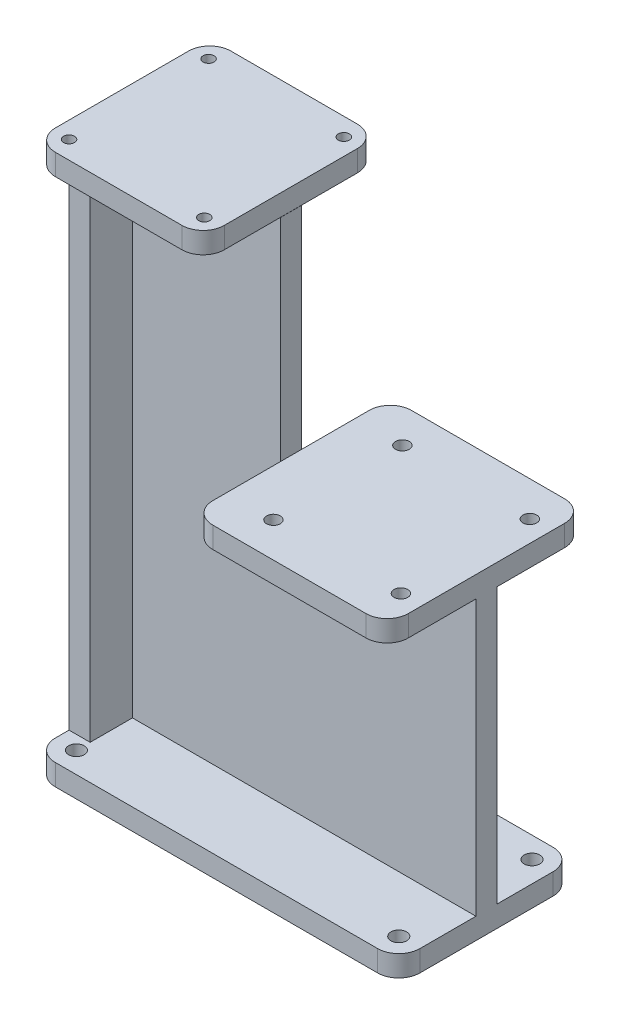
SolidWorks part; units mm, degrees
ref_plane "Front Plane" through (0, 0, 0) normal (0, 0, 1) x (1, 0, 0)
ref_plane "Top Plane" through (0, 0, 0) normal (0, 1, 0) x (1, 0, 0)
ref_plane "Right Plane" through (0, 0, 0) normal (1, 0, 0) x (0, 0, -1)
sketch "Skt - Base w mounting holes" plane through (0, 0, 0) normal (0, 1, 0) x (1, 0, 0)
  line L0 (-38.125, 20.75) -> (38.125, 20.75)
  line L1 (-38.125, -15.75) -> (38.125, -15.75) construction
  line L2 (-38.125, -15.75) -> (-38.125, 15.75) construction
  line L3 (-38.125, 15.75) -> (38.125, 15.75) construction
  line L4 (38.125, -15.75) -> (38.125, 15.75) construction
  line L5 (-38.125, -15.75) -> (38.125, 15.75) construction
  line L6 (-38.125, 15.75) -> (38.125, -15.75) construction
  line L7 (43.125, -15.75) -> (43.125, 15.75)
  line L8 (-38.125, -20.75) -> (38.125, -20.75)
  line L9 (-43.125, -15.75) -> (-43.125, 15.75)
  line L10 (-43.125, -20.75) -> (43.125, -20.75) construction
  line L11 (-43.125, -20.75) -> (-43.125, 20.75) construction
  line L12 (43.125, -20.75) -> (43.125, 20.75) construction
  line L13 (-43.125, 20.75) -> (43.125, 20.75) construction
  circle A0 centre (-38.125, 15.75) radius 1.85
  circle A1 centre (38.125, 15.75) radius 1.85
  circle A2 centre (38.125, -15.75) radius 1.85
  circle A3 centre (-38.125, -15.75) radius 1.85
  arc A4 (-38.125, -20.75) -> (-43.125, -15.75) centre (-38.125, -15.75) cw
  arc A5 (43.125, -15.75) -> (38.125, -20.75) centre (38.125, -15.75) cw
  arc A6 (38.125, 20.75) -> (43.125, 15.75) centre (38.125, 15.75) cw
  arc A7 (-38.125, 20.75) -> (-43.125, 15.75) centre (-38.125, 15.75) ccw
  point P0 (0, 0)
  dimension "D3" = 3.7
  dimension "D5" = 5
  dimension "D1" = 31.5
  dimension "D2" = 76.25
  dimension "D4" = 5
extrude "Ext - Base Plate w Mounting Holes" add sketch "Skt - Base w mounting holes" along normal blind 5 contours L8 A5 L7 A6 L0 A7 L9 A4
sketch "Skt - Upward Ridge" plane through (0, 5, 0) normal (0, 1, 0) x (1, 0, 0)
  line L0 (-43.125, 0) -> (43.125, 0) construction
  line L1 (-43.125, 15.75) -> (-43.125, -15.75) construction
  line L2 (43.125, -15.75) -> (43.125, 15.75) construction
  line L4 (-43.125, -2.5) -> (43.125, -2.5)
  line L5 (-43.125, -2.5) -> (-43.125, 2.5)
  line L6 (-43.125, 2.5) -> (43.125, 2.5)
  line L7 (43.125, -2.5) -> (43.125, 2.5)
  line L8 (-43.125, -2.5) -> (43.125, 2.5) construction
  line L9 (-43.125, 2.5) -> (43.125, -2.5) construction
  point P6 (0, 0)
  dimension "D1" = 5
extrude "Ext - Upward Flange" add sketch "Skt - Upward Ridge" along normal blind 65
sketch "Skt - GPS Nest" plane through (0, 70, 0) normal (0, 1, 0) x (1, 0, 0)
  line L0 (-43.125, 0) -> (43.125, 0) construction
  line L1 (-43.125, 2.5) -> (-43.125, -2.5) construction
  line L2 (43.125, -2.5) -> (43.125, 2.5) construction
  line L3 (43.125, -15.75) -> (43.125, -2.5) construction
  line L4 (1.875, 23.5) -> (38.125, 23.5)
  line L5 (-3.125, 18.5) -> (-3.125, -18.5)
  line L6 (1.875, -23.5) -> (38.125, -23.5)
  line L7 (43.125, 18.5) -> (43.125, -18.5)
  line L8 (-3.125, 23.5) -> (43.125, -23.5) construction
  line L9 (-3.125, -23.5) -> (43.125, 23.5) construction
  arc A0 (38.125, 23.5) -> (43.125, 18.5) centre (38.125, 18.5) cw
  arc A1 (-3.125, -18.5) -> (1.875, -23.5) centre (1.875, -18.5) ccw
  arc A2 (1.875, 23.5) -> (-3.125, 18.5) centre (1.875, 18.5) ccw
  arc A3 (38.125, -23.5) -> (43.125, -18.5) centre (38.125, -18.5) ccw
  point P6 (20, 0)
  dimension "D3" = 5
  dimension "D1" = 47
  dimension "D2" = 40
extrude "Ext - PIX Platform" add sketch "Skt - GPS Nest" along normal blind 5
sketch "Sketch7" plane through (0, 75, 0) normal (0, 1, 0) x (1, 0, 0)
  line L0 (-3.125, 0) -> (43.125, 0) construction
  line L1 (-3.125, 18.5) -> (-3.125, -18.5) construction
  line L2 (43.125, -18.5) -> (43.125, 18.5) construction
  line L3 (43.125, 0) -> (32.9734, 0) construction
  line L4 (7.975, -15.25) -> (38.125, -15.25) construction
  line L5 (7.975, -15.25) -> (7.975, 15.25) construction
  line L6 (38.125, -15.25) -> (38.125, 15.25) construction
  line L7 (7.975, 15.25) -> (38.125, 15.25) construction
  line L8 (7.975, -15.25) -> (38.125, 15.25) construction
  line L9 (38.125, -15.25) -> (7.975, 15.25) construction
  circle A0 centre (7.975, 15.25) radius 1.625
  circle A1 centre (38.125, 15.25) radius 1.625
  circle A2 centre (38.125, -15.25) radius 1.625
  circle A3 centre (7.975, -15.25) radius 1.625
  point P8 (23.05, 0)
  point P17 (43.125, 0)
  dimension "D4" = 3.25
  dimension "D1" = 30.5
  dimension "D2" = 5
  dimension "D3" = 30.15
extrude "Pix Mount Holes" cut sketch "Sketch7" against normal up to next
sketch "Sketch8" plane through (0, 70, 0) normal (0, 1, 0) x (1, 0, 0)
  line L1 (-43.125, 2.5) -> (-3.125, 2.5)
  line L2 (-43.125, 2.5) -> (-43.125, -2.5)
  line L3 (-43.125, -2.5) -> (-3.125, -2.5)
  line L4 (-3.125, 2.5) -> (-3.125, -2.5)
extrude "GPS Flange" add sketch "Sketch8" along normal blind 55
sketch "Sketch9" plane through (0, 125, 0) normal (0, 1, 0) x (1, 0, 0)
  line L0 (-43.125, 0) -> (-3.125, 0) construction
  line L1 (-43.125, 2.5) -> (-43.125, -2.5) construction
  line L2 (-3.125, -2.5) -> (-3.125, 2.5) construction
  line L3 (-38.125, -20.75) -> (38.125, -20.75) construction
  line L4 (-38.0944, 20.75) -> (-8.1556, 20.75)
  line L5 (-43.0944, 15.75) -> (-43.0944, -15.75)
  line L6 (-38.0944, -20.75) -> (-8.1556, -20.75)
  line L7 (-3.1556, 15.75) -> (-3.1556, -15.75)
  line L8 (-43.0944, 20.75) -> (-3.1556, -20.75) construction
  line L9 (-43.0944, -20.75) -> (-3.1556, 20.75) construction
  line L11 (-39.125, 16.5) -> (-7.125, 16.5) construction
  line L12 (-39.125, 16.5) -> (-39.125, -16.5) construction
  line L13 (-39.125, -16.5) -> (-7.125, -16.5) construction
  line L14 (-7.125, 16.5) -> (-7.125, -16.5) construction
  line L15 (-39.125, 16.5) -> (-7.125, -16.5) construction
  line L16 (-39.125, -16.5) -> (-7.125, 16.5) construction
  circle A0 centre (-39.125, 16.5) radius 1.3
  circle A1 centre (-7.125, 16.5) radius 1.3
  circle A2 centre (-7.125, -16.5) radius 1.3
  circle A3 centre (-39.125, -16.5) radius 1.3
  arc A4 (-43.0944, 15.75) -> (-38.0944, 20.75) centre (-38.0944, 15.75) cw
  arc A5 (-3.1556, -15.75) -> (-8.1556, -20.75) centre (-8.1556, -15.75) cw
  arc A6 (-3.1556, 15.75) -> (-8.1556, 20.75) centre (-8.1556, 15.75) ccw
  arc A7 (-43.0944, -15.75) -> (-38.0944, -20.75) centre (-38.0944, -15.75) ccw
  point P6 (-23.125, 0)
  point P13 (-23.125, 0)
  dimension "D3" = 2.6
  dimension "D4" = 5
  dimension "D1" = 32
  dimension "D2" = 33
extrude "GPS Platform" add sketch "Sketch9" along normal blind 5
sketch "Sketch10" plane through (-43.125, 0, 0) normal (-1, 0, 0) x (0, 0, 1)
  line L1 (-15.75, 125) -> (-2.5, 125) construction
  line L2 (-2.5, 5) -> (-12.5, 5)
  line L5 (0, 130) -> (0, 0) construction
  line L6 (-15.75, 130) -> (15.75, 130) construction
  line L15 (-2.5, 5) -> (-2.5, 125)
  line L20 (-2.5, 125) -> (-12.5, 125)
  line L21 (-12.5, 5) -> (-12.5, 125)
  line L22 (2.5, 125) -> (12.5, 125)
  line L23 (12.5, 5) -> (12.5, 125)
  line L24 (2.5, 5) -> (12.5, 5)
  line L25 (2.5, 5) -> (2.5, 125)
  point P4 (0, 0)
  dimension "D1" = 10
extrude "Bracing" add sketch "Sketch10" against normal blind 5
